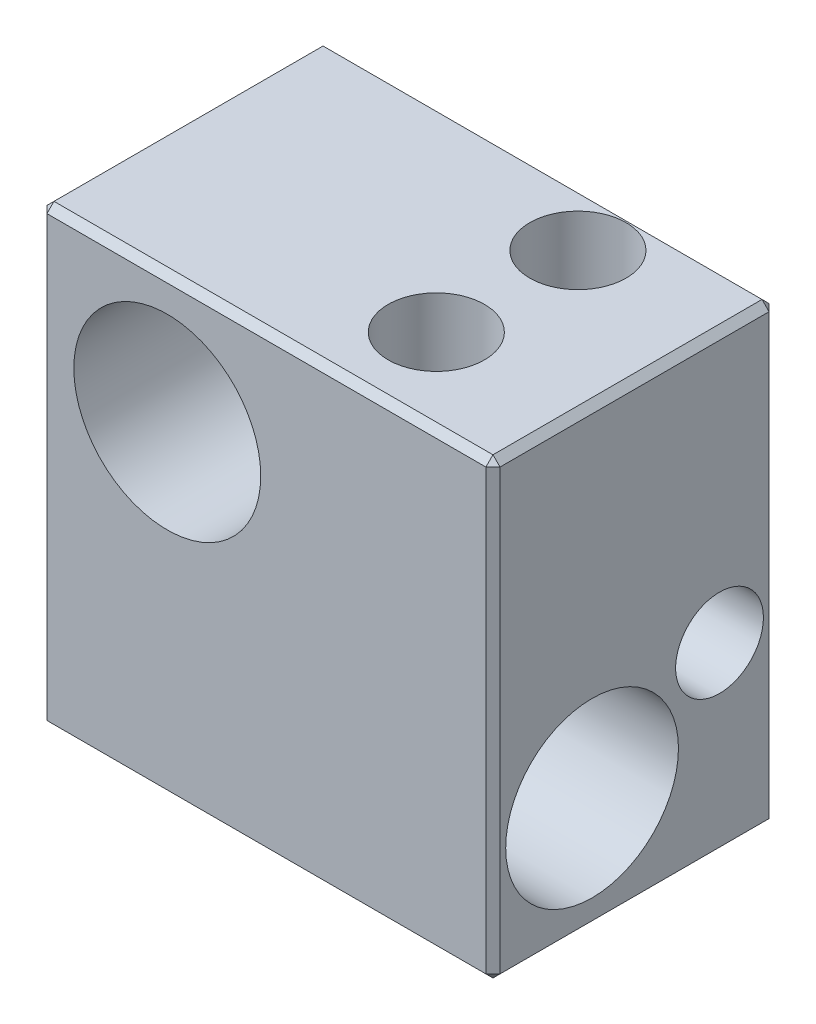
SolidWorks part; units mm, degrees
ref_plane "Plan de face" through (0, 0, 0) normal (0, 0, 1) x (1, 0, 0)
ref_plane "Plan de dessus" through (0, 0, 0) normal (0, 1, 0) x (1, 0, 0)
ref_plane "Plan de droite" through (0, 0, 0) normal (1, 0, 0) x (0, 0, -1)
sketch "Esquisse1" plane through (0, 0, 0) normal (0, 0, 1) x (1, 0, 0)
  line L1 (0, 0) -> (16, 0)
  line L2 (0, 0) -> (0, 16)
  line L3 (0, 16) -> (16, 16)
  line L4 (16, 0) -> (16, 16)
  dimension "D1" = 16
  dimension "D2" = 16
extrude "Boss.-Extru.1" add sketch "Esquisse1" along normal blind 10
sketch "Esquisse2" plane through (0, 0, 10) normal (0, 0, 1) x (1, 0, 0)
  line L0 (16, 16) -> (0, 16) construction
  line L2 (0, 16) -> (0, 0) construction
  circle A0 centre (4.5, 11.5) radius 3
  point P6 (0, 14.3311)
  point P7 (7.9268, 18.1505)
  dimension "D1" = 6
  dimension "D2" = 4.5
  dimension "D3" = 4.5
hole_wizard "Dégagement M61" positions "Esquisse4" profile "Esquisse3" hole size "M6" standard "ISO" end condition through all
sketch "Esquisse4" plane through (0, 0, 10) normal (0, 0, 1) x (1, 0, 0)
  point P0 (4.5, 11.5)
sketch "Esquisse3" plane through (4.5, 11.5, 10) normal (1, 0, 0) x (0, -1, 0)
  line L0 (0, 0) -> (0, 10)
  line L1 (0, 10) -> (3.3, 10)
  line L2 (3.3, 10) -> (3.3, 0)
  line L5 (3.3, 0) -> (0, 0)
  line L11 (0, -6.35) -> (0, 107.95) construction
  dimension "Diamètre du perçage jusqu'au prochain" = 6.6
  dimension "Profondeur du perçage jusqu'au prochain" = 10
sketch "Esquisse5" plane through (16, 0, 0) normal (1, 0, 0) x (0, 0, -1)
  line L0 (-10, 0) -> (0, 0) construction
  line L1 (-10, 0) -> (-10, 16) construction
  line L2 (0, 0) -> (0, 16) construction
  circle A0 centre (-6.5, 4) radius 3
  circle A1 centre (-2, 6.5) radius 1.5
  dimension "D1" = 6
  dimension "D2" = 3
  dimension "D3" = 4
  dimension "D4" = 3.5
  dimension "D5" = 2
  dimension "D6" = 6.5
hole_wizard "Diamètre du perçage Ø6.1 (6.1)1" positions "Esquisse7" profile "Esquisse6" hole size "Ø6.1" standard "ISO" end condition through all
sketch "Esquisse7" plane through (16, 0, 0) normal (1, 0, 0) x (0, 0, -1)
  point P0 (-6.5, 4)
sketch "Esquisse6" plane through (16, 4, 6.5) normal (0, 1, 0) x (0, 0, -1)
  line L0 (0, 0) -> (0, 16)
  line L1 (0, 16) -> (3.05, 16)
  line L2 (3.05, 16) -> (3.05, 0)
  line L5 (3.05, 0) -> (0, 0)
  line L11 (0, -6.35) -> (0, 107.95) construction
  dimension "Diamètre du perçage jusqu'au prochain" = 6.1
  dimension "Profondeur du perçage jusqu'au prochain" = 16
hole_wizard "Diamètre du perçage Ø3.1 (3.1)1" positions "Esquisse9" profile "Esquisse8" hole size "Ø3.1" standard "ISO" end condition through all
sketch "Esquisse9" plane through (16, 0, 0) normal (1, 0, 0) x (0, 0, -1)
  point P0 (-2, 6.5)
sketch "Esquisse8" plane through (16, 6.5, 2) normal (0, 1, 0) x (0, 0, -1)
  line L0 (0, 0) -> (0, 16)
  line L1 (0, 16) -> (1.55, 16)
  line L2 (1.55, 16) -> (1.55, 0)
  line L5 (1.55, 0) -> (0, 0)
  line L11 (0, -6.35) -> (0, 107.95) construction
  dimension "Diamètre du perçage jusqu'au prochain" = 3.1
  dimension "Profondeur du perçage jusqu'au prochain" = 16
sketch "Esquisse10" plane through (0, 16, 0) normal (0, 1, 0) x (1, 0, 0)
  line L0 (16, -10) -> (16, 0) construction
  line L1 (16, -10) -> (0, -10) construction
  line L2 (16, 0) -> (0, 0) construction
  circle A0 centre (11, -7) radius 1.5
  circle A1 centre (11, -2) radius 1.5
  dimension "D1" = 3
  dimension "D2" = 3
  dimension "D3" = 5
  dimension "D4" = 5
  dimension "D5" = 3
  dimension "D6" = 2
hole_wizard "Dégagement M31" positions "Esquisse14" profile "Esquisse13" hole size "M3" standard "ISO"
sketch "Esquisse14" plane through (0, 16, 0) normal (0, 1, 0) x (1, 0, 0)
  point P0 (11, -7)
sketch "Esquisse13" plane through (11, 16, 7) normal (1, 0, 0) x (0, 0, 1)
  line L0 (0, 0) -> (0, 12.0215)
  line L1 (0, 12.0215) -> (1.7, 11)
  line L2 (1.7, 11) -> (1.7, 0)
  line L5 (1.7, 0) -> (0, 0)
  line L10 (0, 12.0215) -> (-1.7, 11) construction
  line L11 (0, -6.35) -> (0, 107.95) construction
  dimension "Diamètre du perçage" = 3.4
  dimension "Profondeur du perçage" = 11
  dimension "Angle de pointe" = 118
hole_wizard "Dégagement M32" positions "Esquisse16" profile "Esquisse15" hole size "M3" standard "ISO"
sketch "Esquisse16" plane through (0, 16, 0) normal (0, 1, 0) x (1, 0, 0)
  point P0 (11, -2)
sketch "Esquisse15" plane through (11, 16, 2) normal (1, 0, 0) x (0, 0, 1)
  line L0 (0, 0) -> (0, 10.5215)
  line L1 (0, 10.5215) -> (1.7, 9.5)
  line L2 (1.7, 9.5) -> (1.7, 0)
  line L5 (1.7, 0) -> (0, 0)
  line L10 (0, 10.5215) -> (-1.7, 9.5) construction
  line L11 (0, -6.35) -> (0, 107.95) construction
  dimension "Diamètre du perçage" = 3.4
  dimension "Profondeur du perçage" = 9.5
  dimension "Angle de pointe" = 118
chamfer "Chanfrein1" distance 0.25 angle 45 12 edges at (0, 8, 0) (0, 8, 10) (8, 0, 10) (0, 0, 5) (8, 0, 0) (16, 8, 10) (16, 0, 5) (16, 8, 0) (8, 16, 10) (16, 16, 5) (8, 16, 0) (0, 16, 5)
